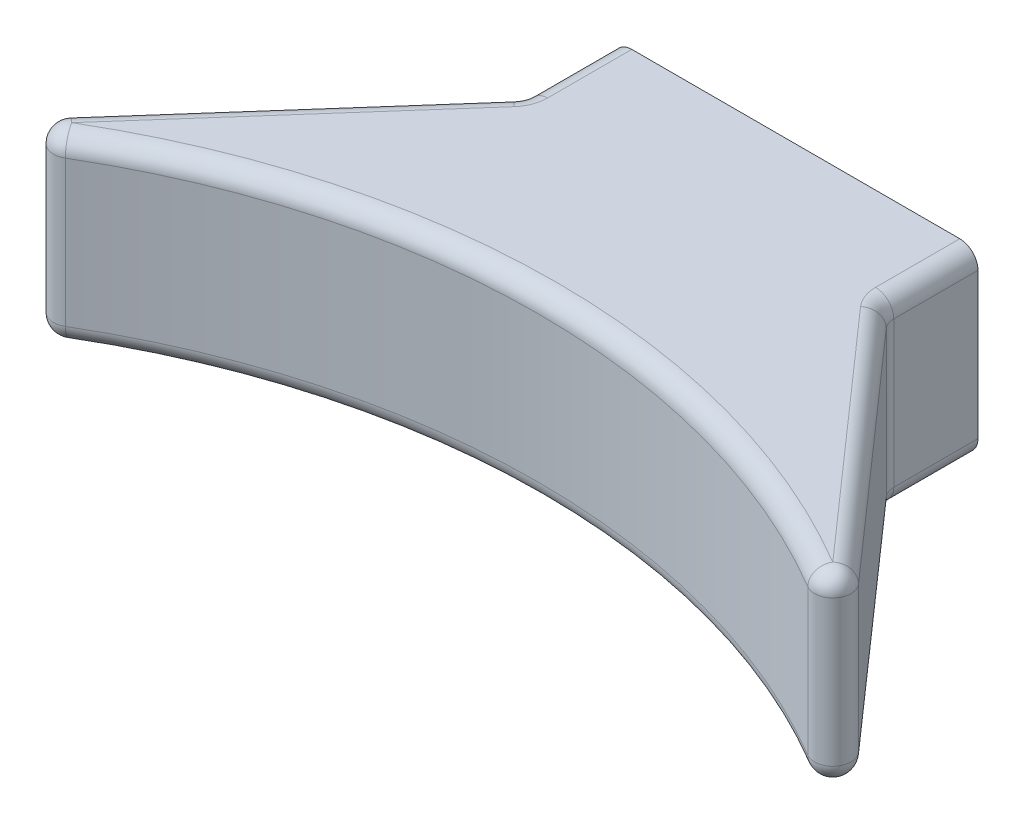
SolidWorks part; units mm, degrees
ref_plane "Front" through (0, 0, 0) normal (0, 0, 1) x (1, 0, 0)
ref_plane "Top" through (0, 0, 0) normal (0, 1, 0) x (1, 0, 0)
ref_plane "Right" through (0, 0, 0) normal (1, 0, 0) x (0, 0, -1)
sketch "Esquisse1" plane through (0, 0, 0) normal (0, 0, 1) x (1, 0, 0)
  line L1 (-12.7, 6.35) -> (12.7, 6.35)
  line L2 (-12.7, 6.35) -> (-12.7, -6.35)
  line L3 (-12.7, -6.35) -> (12.7, -6.35)
  line L4 (12.7, 6.35) -> (12.7, -6.35)
  line L5 (-12.7, 6.35) -> (12.7, -6.35) construction
  line L6 (-12.7, -6.35) -> (12.7, 6.35) construction
  point P0 (0, 0)
  dimension "D1" = 25.4
  dimension "D2" = 12.7
extrude "Boss.-Extru.1" add sketch "Esquisse1" along normal blind 6.35
sketch "Esquisse2" plane through (0, -6.35, 0) normal (0, -1, 0) x (1, 0, 0)
  line L0 (-12.7, 6.35) -> (-27.4744, 23.1026)
  line L1 (27.4744, 23.1026) -> (12.7, 6.35)
  line L6 (-12.7, 0) -> (12.7, 0)
  line L7 (12.7, 0) -> (12.7, 6.35)
  line L8 (12.7, 6.35) -> (-12.7, 6.35)
  line L9 (-12.7, 6.35) -> (-12.7, 0)
  line L10 (-12.7, 0) -> (12.7, 0)
  line L11 (12.7, 0) -> (12.7, 6.35)
  line L13 (-12.7, 6.35) -> (-12.7, 0)
  arc A0 (-25.875, 25.0356) -> (25.875, 25.0356) centre (0, 68.7519) ccw
  arc A1 (25.875, 25.0356) -> (27.4744, 23.1026) centre (26.5219, 23.9426) cw
  arc A2 (-27.4744, 23.1026) -> (-25.875, 25.0356) centre (-26.5219, 23.9426) cw
  point P5 (39.826, 29.5164)
  point P8 (0, 0)
  point P9 (0, 0)
  point P11 (0, 66.6378)
  point P12 (0, 0)
  point P15 (38.1, 35.1509)
  point P18 (-38.1, 35.1509)
  dimension "D1" = 50.8
  dimension "D4" = 1.27
  dimension "D2" = 38.1
  dimension "D3" = 38.1
  dimension "D5" = 0
extrude "Boss.-Extru.2" add sketch "Esquisse2" against normal blind 12.7
fillet "Congé1" radius 1.27 16 edges at (-12.7, 6.35, 3.175) (-12.7, -6.35, 3.175) (12.7, 6.35, 3.175) (12.7, -6.35, 3.175) (27.5004, -6.35, 24.7523) (27.5004, 6.35, 24.7523) (-20.0872, -6.35, 14.7263) (-20.0872, 6.35, 14.7263) (-27.5004, -6.35, 24.7523) (-27.5004, 6.35, 24.7523) (20.0872, -6.35, 14.7263) (20.0872, 6.35, 14.7263) (12.7, 0, 6.35) (-12.7, 0, 6.35) (0, -6.35, 17.9519) (0, 6.35, 17.9519)
sketch "Esquisse3" plane through (0, 0, 0) normal (0, 0, -1) x (-1, 0, 0)
  line L0 (-12.7, -5.08) -> (-12.7, 5.08) construction
  line L1 (12.7, 5.08) -> (12.7, -5.08) construction
  circle A0 centre (-6.35, 0) radius 1.5
  circle A1 centre (6.35, 0) radius 1.5
  dimension "D1" = 3
  dimension "D2" = 3
  dimension "D3" = 6.35
  dimension "D4" = 6.35
extrude "Enlèv. mat.-Extru.1" cut sketch "Esquisse3" against normal blind 9.525
